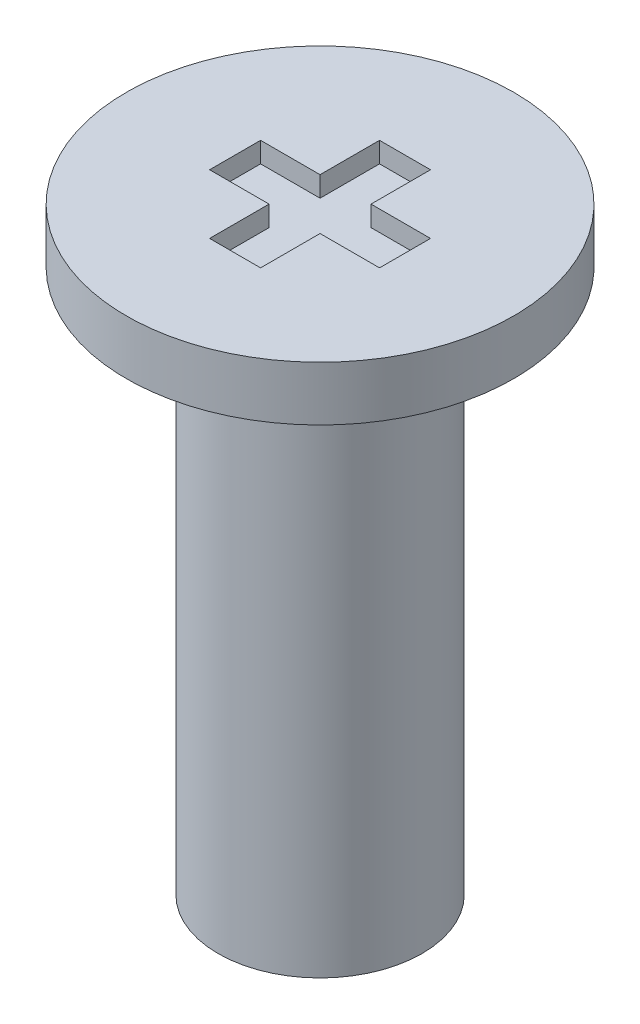
SolidWorks part; units mm, degrees
material "S45C"
ref_plane "正面" through (0, 0, 0) normal (0, 0, 1) x (1, 0, 0)
ref_plane "平面" through (0, 0, 0) normal (0, 1, 0) x (1, 0, 0)
ref_plane "右側面" through (0, 0, 0) normal (1, 0, 0) x (0, 0, -1)
sketch "ｽｹｯﾁ1" plane through (0, 0, 0) normal (0, 0, 1) x (1, 0, 0)
  line L0 (0, 0) -> (2.85, 0)
  line L1 (2.85, 0) -> (2.85, -0.8)
  line L2 (2.85, -0.8) -> (1.5, -0.8)
  line L3 (1.5, -0.8) -> (1.5, -8.8)
  line L4 (1.5, -8.8) -> (0, -8.8)
  line L5 (0, -8.8) -> (0, 0)
  dimension "D1" = 2.85
  dimension "D2" = 0.8
  dimension "D3" = 1.5
  dimension "D4" = 8
revolve "回転1" add sketch "ｽｹｯﾁ1" angle 360 about L5
sketch "ｽｹｯﾁ2" plane through (0, 0, 0) normal (0, 1, 0) x (1, 0, 0)
  line L1 (-0.375, 0) -> (0.375, 0)
  line L2 (-0.375, 0) -> (-0.375, 1.25)
  line L3 (-0.375, 1.25) -> (0.375, 1.25)
  line L4 (0.375, 0) -> (0.375, 1.25)
  line L5 (-0.375, 0) -> (0.375, 1.25) construction
  line L6 (-0.375, 1.25) -> (0.375, 0) construction
  point P4 (0, 0.625)
  dimension "D1" = 0
  dimension "D2" = 0.75
  dimension "D3" = 1.25
  dimension "D4" = 0
extrude "ｶｯﾄ - 押し出し1" cut sketch "ｽｹｯﾁ2" against normal blind 0.3
pattern_circular "円形ﾊﾟﾀｰﾝ1" count 4 over 360 about axis through (0, 0, 0) along (0, 1, 0) of "ｶｯﾄ - 押し出し1"
